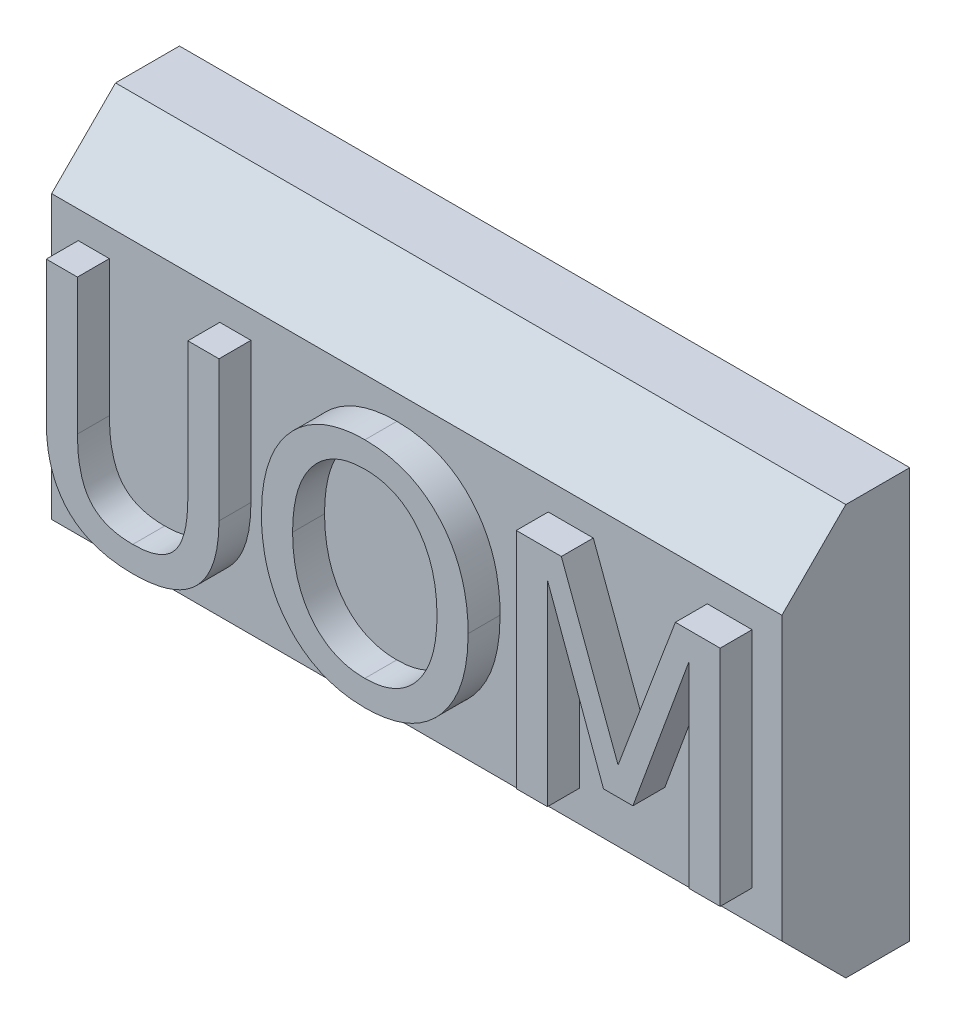
SolidWorks part; units mm, degrees
ref_plane "Front Plane" through (0, 0, 0) normal (0, 0, 1) x (1, 0, 0)
ref_plane "Top Plane" through (0, 0, 0) normal (0, 1, 0) x (1, 0, 0)
ref_plane "Right Plane" through (0, 0, 0) normal (1, 0, 0) x (0, 0, -1)
sketch "Sketch3" plane through (0, 0, 0) normal (0, 0, 1) x (1, 0, 0)
  text T0 "UOM" font "SolidWorks GDT" height 3.5
sketch "Sketch4" plane through (0, 0, 0) normal (0, 0, 1) x (1, 0, 0)
  line L0 (0, 5.7766) -> (0, -1.8486) construction
  line L1 (0, 3.9291) -> (11.4273, 3.9291)
  line L2 (0, 3.9291) -> (0, -0.4866)
  line L3 (0, -0.4866) -> (11.4273, -0.4866)
  line L4 (11.4273, 3.9291) -> (11.4273, -0.4866)
  line L5 (0, -1.1) -> (0, 1.1) construction
  point P9 (0, 3.865)
  point P10 (0, -0.4866)
  point P11 (0, 0)
  point P12 (0, 0)
  point P13 (0, 0)
  point P14 (0, 0)
  point P15 (0, 0)
  point P16 (0, 0)
  point P17 (0, 0)
  point P18 (0, 0)
sketch "Sketch6" plane through (0, 0, 0) normal (1, 0, 0) x (0, 0, -1)
  line L0 (0, 5.7766) -> (0, -1.8486) construction
  line L1 (1, 4.9291) -> (2, 4.9291)
  line L2 (0, 3.9291) -> (0, -0.4866)
  line L3 (1, -1.4866) -> (2, -1.4866)
  line L4 (2, 4.9291) -> (2, -1.4866)
  line L6 (0, 3.9291) -> (1, 4.9291)
  line L7 (0, -0.4866) -> (1, -1.4866)
  line L8 (0, 3.9291) -> (0, -0.4866) construction
  line L9 (0, 3.9291) -> (0, -0.4866) construction
  point P0 (0, 4.9291)
  point P2 (0, -1.4866)
  point P4 (0, 0)
  point P5 (0, 3.9291)
  point P8 (0, 0)
  point P9 (0, 0)
  point P14 (0, 0)
  point P15 (0, 3.9987)
  point P18 (0, -0.5207)
  point P19 (0, 4.4724)
  point P20 (0, 0)
  point P21 (0, 4.1833)
  point P22 (0, 3.9987)
  point P25 (0, -0.4617)
  point P26 (0, -0.3569)
  point P27 (0, -0.4866)
  dimension "D1" = 1
  dimension "D2" = 45
  dimension "D3" = 1
  dimension "D4" = 45
  dimension "D5" = 1
extrude "Boss-Extrude5" add sketch "Sketch6" along normal up to vertex (11.4273 mm away) up to point (11.4273, -0.4866, 0)
extrude "Boss-Extrude6" add sketch "Sketch3" along normal blind 0.5
